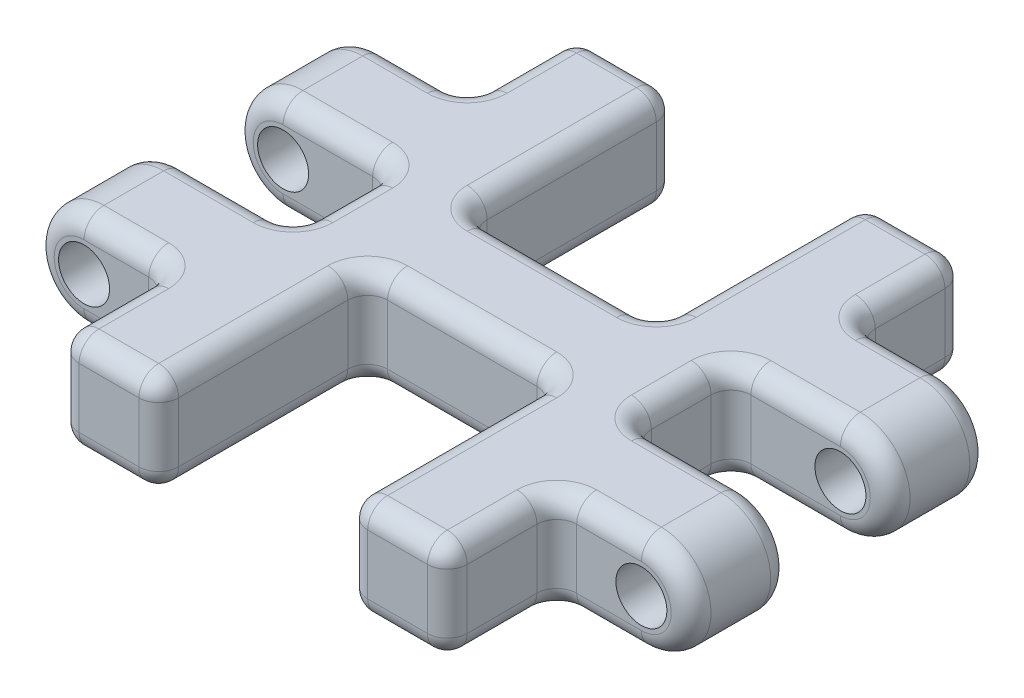
SolidWorks part; units mm, degrees
ref_plane "Front Plane" through (0, 0, 0) normal (0, 0, 1) x (1, 0, 0)
ref_plane "Top Plane" through (0, 0, 0) normal (0, 1, 0) x (1, 0, 0)
ref_plane "Right Plane" through (0, 0, 0) normal (1, 0, 0) x (0, 0, -1)
sketch "Sketch1" plane through (0, 0, 0) normal (0, 0, 1) x (1, 0, 0)
  line L0 (17.78, 0) -> (-17.78, 0) construction
  line L1 (17.78, -3.175) -> (-17.78, -3.175)
  line L2 (17.78, 3.175) -> (-17.78, 3.175)
  arc A0 (17.78, -3.175) -> (17.78, 3.175) centre (17.78, 0) ccw
  arc A1 (-17.78, 3.175) -> (-17.78, -3.175) centre (-17.78, 0) ccw
  point P2 (0, 0)
  dimension "D1" = 3.175
  dimension "D2" = 35.56
extrude "Boss-Extrude1" add sketch "Sketch1" along normal mid plane 33.02
sketch "Sketch2" plane through (0, 3.175, 0) normal (0, 1, 0) x (1, 0, 0)
  line L0 (17.78, 16.51) -> (-17.78, 16.51) construction
  line L1 (6.0325, 3.175) -> (-6.0325, 3.175)
  line L2 (6.0325, 3.175) -> (6.0325, 16.51)
  line L3 (6.0325, 16.51) -> (-6.0325, 16.51)
  line L4 (-6.0325, 3.175) -> (-6.0325, 16.51)
  line L5 (6.0325, 3.175) -> (-6.0325, 16.51) construction
  line L6 (6.0325, 16.51) -> (-6.0325, 3.175) construction
  line L7 (-20.955, 16.51) -> (-20.955, -16.51) construction
  line L8 (-12.3825, 16.51) -> (-20.955, 16.51)
  line L9 (-12.3825, 16.51) -> (-12.3825, 9.525)
  line L10 (-12.3825, 9.525) -> (-20.955, 9.525)
  line L11 (-20.955, 16.51) -> (-20.955, 9.525)
  line L12 (0, -3.4925) -> (0, 3.4925) construction
  line L13 (12.3825, 16.51) -> (12.3825, 9.525)
  line L14 (12.3825, 16.51) -> (20.955, 16.51)
  line L15 (20.955, 16.51) -> (20.955, 9.525)
  line L16 (12.3825, 9.525) -> (20.955, 9.525)
  line L17 (-3.4925, 0) -> (3.4925, 0) construction
  line L18 (-10.795, -3.175) -> (-20.955, -3.175)
  line L19 (-10.795, -3.175) -> (-10.795, 3.175)
  line L20 (-10.795, 3.175) -> (-20.955, 3.175)
  line L21 (-20.955, -3.175) -> (-20.955, 3.175)
  line L22 (-10.795, -3.175) -> (-20.955, 3.175) construction
  line L23 (-10.795, 3.175) -> (-20.955, -3.175) construction
  line L24 (10.795, -3.175) -> (20.955, -3.175)
  line L25 (10.795, -3.175) -> (10.795, 3.175)
  line L26 (20.955, -3.175) -> (20.955, 3.175)
  line L27 (10.795, 3.175) -> (20.955, 3.175)
  point P0 (0, 9.8425)
  point P22 (-15.875, 0)
  dimension "D1" = 13.335
  dimension "D2" = 12.065
  dimension "D3" = 6.35
  dimension "D4" = 6.985
  dimension "D5" = 6.35
  dimension "D6" = 10.16
extrude "Cut-Extrude1" cut sketch "Sketch2" against normal up to surface (6.35 mm away) up to face at (0, -3.175, 0)
mirror "Mirror1" about plane through (0, 0, 0) normal (0, 0, 1) of "Cut-Extrude1"
sketch "Sketch3" plane through (0, 0, 9.525) normal (0, 0, 1) x (1, 0, 0)
  line L0 (18.161, 0) -> (-18.161, 0) construction
  circle A0 centre (-17.78, 0) radius 1.627
  arc A1 (-17.78, 3.175) -> (-17.78, -3.175) centre (-17.78, 0) ccw construction
  dimension "D1" = 3.254
extrude "Cut-Extrude2" cut sketch "Sketch3" against normal up to surface (19.05 mm away) up to face at (-15.875, 0, -9.525)
mirror "Mirror2" about plane through (0, 0, 0) normal (1, 0, 0) of "Cut-Extrude2"
fillet "Fillet1" radius 1.27 76 edges at (-15.0812, -3.175, 9.525) (-20.955, 0, 9.525) (-14.2875, -3.175, 3.175) (-20.955, 0, 3.175) (-14.2875, -3.175, -3.175) (-20.955, 0, -3.175) (-15.0812, -3.175, -9.525) (-20.955, 0, -9.525) (15.0813, -3.175, -9.525) (20.955, 0, -9.525) (14.2875, -3.175, -3.175) (20.955, 0, -3.175) (14.2875, -3.175, 3.175) (20.955, 0, 3.175) (15.0812, -3.175, 9.525) (20.955, 0, 9.525) (12.3825, 3.175, 13.0175) (9.2075, 3.175, 16.51) (6.0325, 3.175, 9.8425) (0, 3.175, 3.175) (-6.0325, 3.175, 9.8425) (-9.2075, 3.175, 16.51) (-12.3825, 3.175, 13.0175) (-15.0812, 3.175, 9.525) (-14.2875, 3.175, 3.175) (-10.795, 3.175, 0) (-14.2875, 3.175, -3.175) (-15.0812, 3.175, -9.525) (-12.3825, 3.175, -13.0175) (-9.2075, 3.175, -16.51) (-6.0325, 3.175, -9.8425) (0, 3.175, -3.175) (6.0325, 3.175, -9.8425) (9.2075, 3.175, -16.51) (12.3825, 3.175, -13.0175) (15.0812, 3.175, -9.525) (14.2875, 3.175, -3.175) (10.795, 3.175, 0) (14.2875, 3.175, 3.175) (15.0812, 3.175, 9.525) (6.0325, -3.175, 9.8425) (-6.0325, -3.175, 9.8425) (0, -3.175, 3.175) (6.0325, 0, -3.175) (-6.0325, 0, -3.175) (0, -3.175, -3.175) (9.2075, -3.175, -16.51) (-9.2075, -3.175, -16.51) (-6.0325, -3.175, -9.8425) (6.0325, -3.175, -9.8425) (-6.0325, 0, -16.51) (-12.3825, 0, -16.51) (6.0325, 0, 16.51) (12.3825, 0, 16.51) (10.795, -3.175, 0) (12.3825, -3.175, -13.0175) (-12.3825, -3.175, -13.0175) (-10.795, -3.175, 0) (-12.3825, -3.175, 13.0175) (-9.2075, -3.175, 16.51) (9.2075, -3.175, 16.51) (12.3825, -3.175, 13.0175) (6.0325, 0, -16.51) (12.3825, 0, -16.51) (-12.3825, 0, 16.51) (-6.0325, 0, 16.51) (-10.795, 0, -3.175) (-12.3825, 0, 9.525) (-12.3825, 0, -9.525) (12.3825, 0, -9.525) (12.3825, 0, 9.525) (10.795, 0, 3.175) (10.795, 0, -3.175) (-10.795, 0, 3.175) (6.0325, 0, 3.175) (-6.0325, 0, 3.175)
